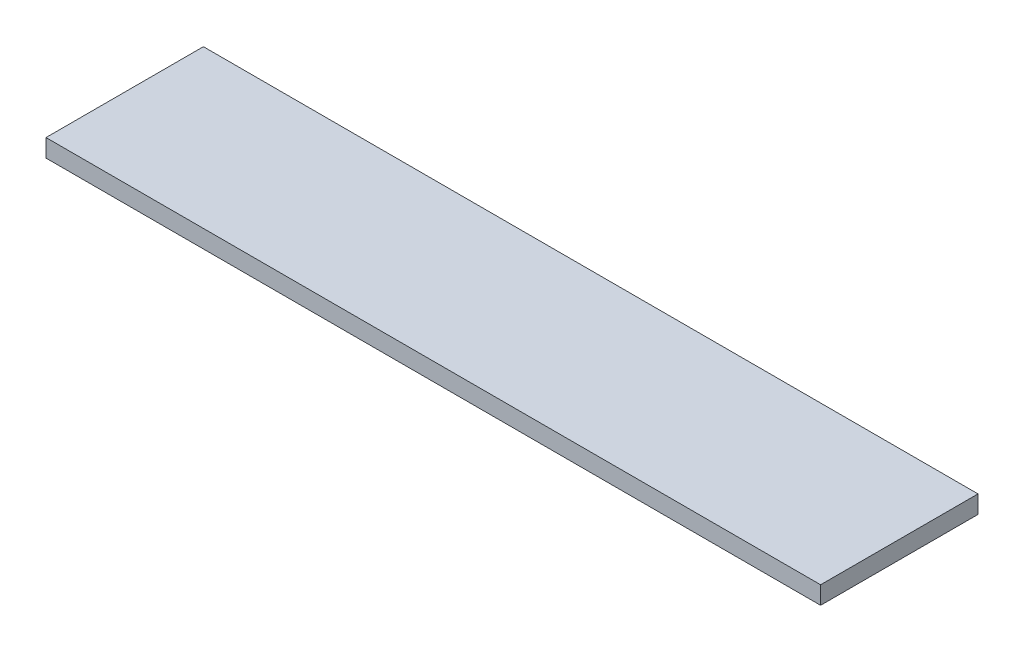
SolidWorks part; units mm, degrees
ref_plane "Front Plane" through (0, 0, 0) normal (0, 0, 1) x (1, 0, 0)
ref_plane "Top Plane" through (0, 0, 0) normal (0, 1, 0) x (1, 0, 0)
ref_plane "Right Plane" through (0, 0, 0) normal (1, 0, 0) x (0, 0, -1)
sketch "Sketch1" plane through (0, 0, 0) normal (0, 1, 0) x (1, 0, 0)
  line L1 (-62.5, 12.7) -> (62.5, 12.7)
  line L2 (-62.5, 12.7) -> (-62.5, -12.7)
  line L3 (-62.5, -12.7) -> (62.5, -12.7)
  line L4 (62.5, 12.7) -> (62.5, -12.7)
  line L5 (-62.5, 12.7) -> (62.5, -12.7) construction
  line L6 (-62.5, -12.7) -> (62.5, 12.7) construction
  point P0 (0, 0)
  dimension "D1" = 25.4
  dimension "D2" = 125
extrude "Boss-Extrude1" add sketch "Sketch1" along normal blind 2.875
